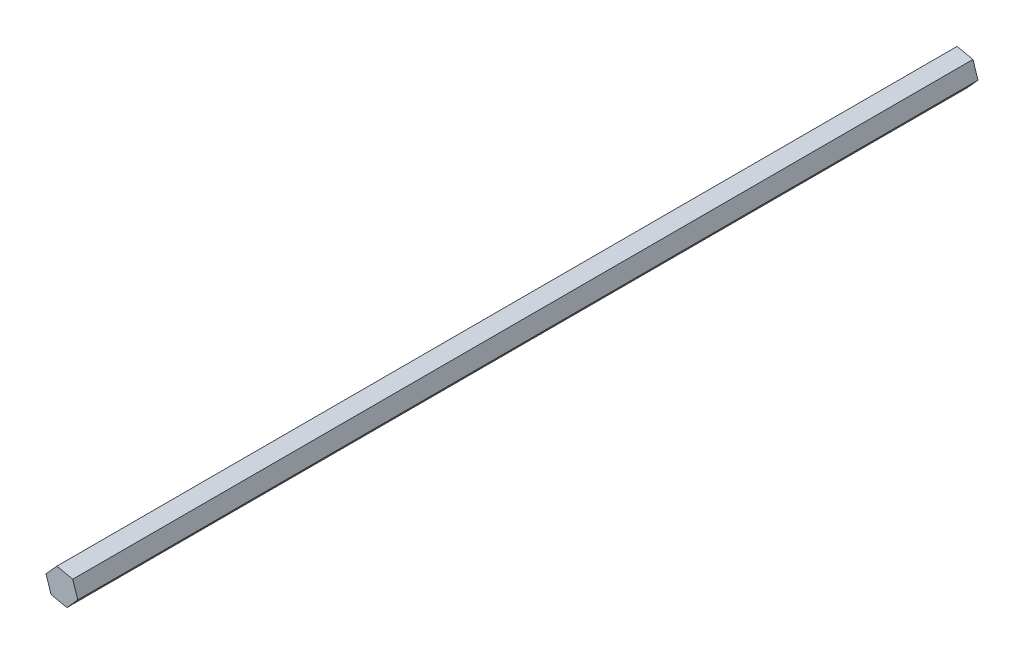
SolidWorks part; units mm, degrees
ref_plane "Front Plane" through (0, 0, 0) normal (0, 0, 1) x (1, 0, 0)
ref_plane "Top Plane" through (0, 0, 0) normal (0, 1, 0) x (1, 0, 0)
ref_plane "Right Plane" through (0, 0, 0) normal (1, 0, 0) x (0, 0, -1)
sketch "Sketch1" plane through (0, 0, 0) normal (0, 0, 1) x (1, 0, 0)
  line L1 (-5.9987, -0.409) -> (-8.2711, 6.5623)
  line L2 (-8.2711, 6.5623) -> (-15.4446, 8.08)
  line L3 (-15.4446, 8.08) -> (-20.3458, 2.6264)
  line L4 (-20.3458, 2.6264) -> (-18.0734, -4.345)
  line L5 (-18.0734, -4.345) -> (-10.8998, -5.8626)
  line L6 (-10.8998, -5.8626) -> (-5.9987, -0.409)
  circle A0 centre (-13.1722, 1.1087) radius 6.35 construction
  dimension "D1" = 12.7
extrude "Boss-Extrude1" add sketch "Sketch1" along normal blind 406.4 contours L3 L4 L5 L6 L1 L2
